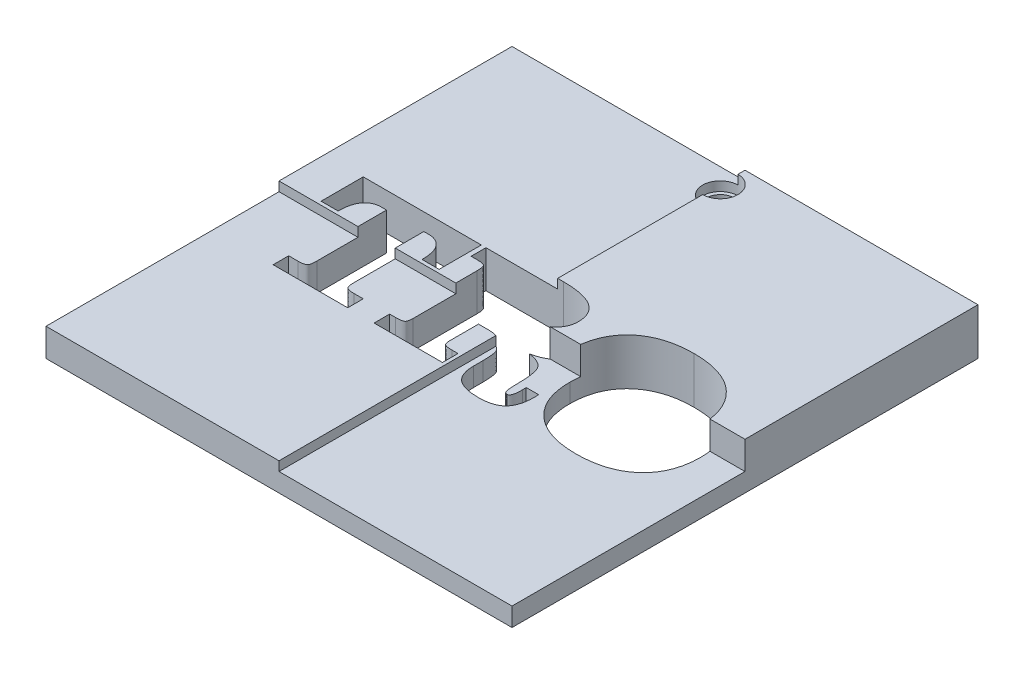
SolidWorks part; units mm, degrees
ref_plane "Front Plane" through (0, 0, 0) normal (0, 0, 1) x (1, 0, 0)
ref_plane "Top Plane" through (0, 0, 0) normal (0, 1, 0) x (1, 0, 0)
ref_plane "Right Plane" through (0, 0, 0) normal (1, 0, 0) x (0, 0, -1)
sketch "Sketch1" plane through (0, 0, 0) normal (0, 1, 0) x (1, 0, 0)
  line L7 (0, 0) -> (50, 0)
  line L8 (0, 0) -> (0, 50)
  line L9 (0, 50) -> (50, 50)
  line L10 (50, 0) -> (50, 50)
  dimension "D1" = 50
  dimension "D2" = 50
extrude "Boss-Extrude1" add sketch "Sketch1" along normal blind 5
sketch "Sketch2" plane through (0, 5, 0) normal (0, 1, 0) x (1, 0, 0)
  line L1 (0, 50) -> (25, 50)
  line L2 (0, 50) -> (0, 25)
  line L3 (0, 25) -> (25, 25)
  line L4 (25, 50) -> (25, 25)
  dimension "D1" = 25
  dimension "D2" = 25
extrude "Cut-Extrude1" cut sketch "Sketch2" against normal blind 1
sketch "Sketch3" plane through (0, 5, 0) normal (0, 1, 0) x (1, 0, 0)
  line L1 (25, 25) -> (0, 25)
  line L2 (25, 25) -> (25, 0)
  line L3 (25, 0) -> (0, 0)
  line L4 (0, 25) -> (0, 0)
extrude "Cut-Extrude2" cut sketch "Sketch3" against normal blind 2
sketch "Sketch4" plane through (0, 5, 0) normal (0, 1, 0) x (1, 0, 0)
  line L0 (25, 0) -> (25, 50) construction
  line L1 (25, 25) -> (50, 25)
  line L2 (25, 25) -> (25, 0)
  line L3 (25, 0) -> (50, 0)
  line L4 (50, 25) -> (50, 0)
extrude "Cut-Extrude4" cut sketch "Sketch4" against normal blind 3
sketch "Sketch6" plane through (0, 5, 0) normal (0, 1, 0) x (1, 0, 0)
  line L0 (25, 25) -> (25, 50) construction
  circle A0 centre (25, 47.3514) radius 1.5
  dimension "D1" = 3
extrude "Cut-Extrude5" cut sketch "Sketch6" against normal blind 10 contours A0
sketch "Sketch9" plane through (0, 5, 0) normal (0, 1, 0) x (1, 0, 0)
  text T0 "TRO" font "Clarendon Blk BT" height 12
extrude "Cut-Extrude6" cut sketch "Sketch9" against normal blind 10
sketch "Sketch12" plane through (0, 5, 0) normal (0, 1, 0) x (1, 0, 0)
  circle A0 centre (23.9335, 26.8997) radius 2.5047
extrude "Cut-Extrude7" cut sketch "Sketch12" against normal blind 10
sketch "Sketch13" plane through (0, 5, 0) normal (0, 1, 0) x (1, 0, 0)
  circle A0 centre (39.2642, 23.9002) radius 5.5468
extrude "Cut-Extrude8" cut sketch "Sketch13" against normal blind 10
sketch "Sketch14" plane through (0, 5, 0) normal (0, 1, 0) x (1, 0, 0)
  circle A0 centre (25, 47.3514) radius 1.8918
extrude "Cut-Extrude9" cut sketch "Sketch14" against normal blind 2
